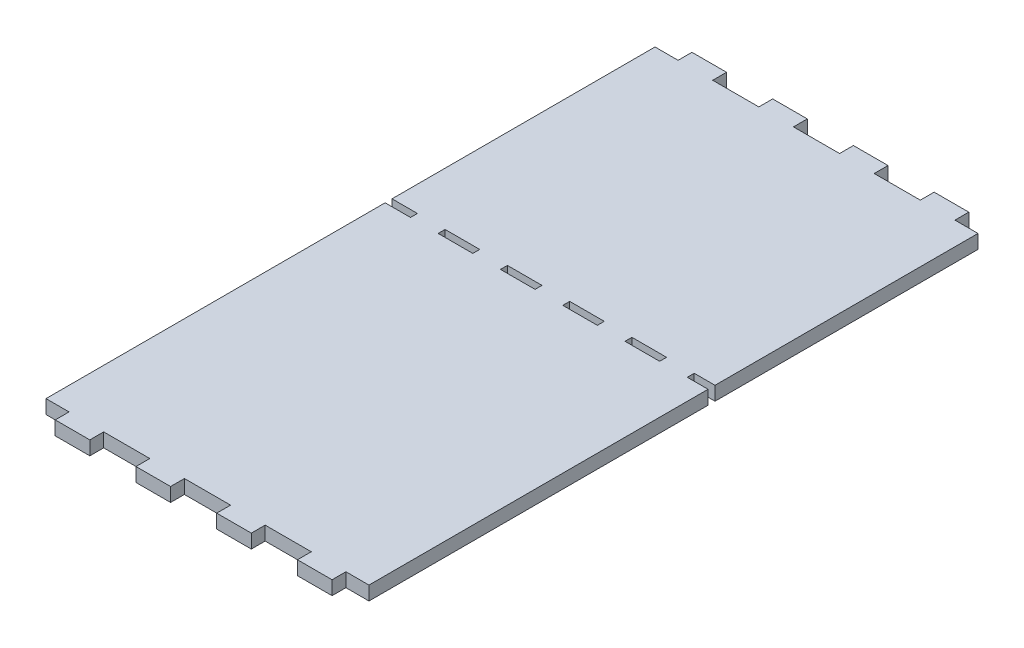
SolidWorks part; units mm, degrees
ref_plane "Plan de face" through (0, 0, 0) normal (0, 0, 1) x (1, 0, 0)
ref_plane "Plan de dessus" through (0, 0, 0) normal (0, 1, 0) x (1, 0, 0)
ref_plane "Plan de droite" through (0, 0, 0) normal (1, 0, 0) x (0, 0, -1)
sketch "Esquisse1" plane through (0, 0, 0) normal (0, 1, 0) x (1, 0, 0)
  line L0 (-140, 138) -> (0, 138) construction
  line L1 (0, 0) -> (-140, 0)
  line L2 (0, 0) -> (0, 276)
  line L3 (0, 276) -> (-140, 276)
  line L4 (-140, 0) -> (-140, 276)
  line L5 (-140, 0) -> (-115, 0)
  line L6 (-140, 0) -> (-140, 6)
  line L7 (-140, 0) -> (-130, 0)
  line L8 (-115, 0) -> (-115, 6)
  line L9 (-115, 6) -> (-95, 6)
  line L10 (-115, 6) -> (-115, 0)
  line L11 (-115, 0) -> (-95, 0)
  line L12 (-95, 6) -> (-95, 0)
  line L13 (-95, 6) -> (-80, 6)
  line L14 (-95, 6) -> (-95, 0)
  line L15 (-95, 0) -> (-80, 0)
  line L16 (-80, 6) -> (-80, 0)
  line L17 (-80, 6) -> (-60, 6)
  line L18 (-80, 6) -> (-80, 0)
  line L19 (-80, 0) -> (-60, 0)
  line L20 (-60, 6) -> (-60, 0)
  line L21 (-60, 6) -> (-45, 6)
  line L22 (-60, 6) -> (-60, 0)
  line L23 (-60, 0) -> (-45, 0)
  line L24 (-45, 6) -> (-45, 0)
  line L25 (-45, 6) -> (-25, 6)
  line L26 (-45, 6) -> (-45, 0)
  line L27 (-45, 0) -> (-25, 0)
  line L28 (-25, 6) -> (-25, 0)
  line L29 (-25, 6) -> (-10, 6)
  line L30 (-25, 6) -> (-25, 0)
  line L31 (-25, 0) -> (-10, 0)
  line L32 (-10, 6) -> (-10, 0)
  line L33 (-10, 6) -> (0, 6)
  line L34 (-10, 6) -> (-10, 0)
  line L35 (-140, 6) -> (-130, 6)
  line L36 (-10, 6) -> (-10, 0)
  line L37 (-140, 6) -> (-140, 0)
  line L38 (-140, 0) -> (-130, 0)
  line L39 (-130, 6) -> (-130, 0)
  line L40 (-10, 270) -> (0, 270)
  line L41 (-140, 0) -> (-140, 6)
  line L43 (-130, 0) -> (-130, 6)
  line L44 (-130, 6) -> (-115, 6)
  line L45 (-130, 6) -> (-130, 0)
  line L46 (-130, 0) -> (-115, 0)
  line L47 (-115, 6) -> (-115, 0)
  line L48 (0, 0) -> (0, 6)
  line L51 (0, 0) -> (0, 6)
  line L52 (0, 276) -> (0, 270)
  line L56 (-115, 270) -> (-115, 276)
  line L57 (-130, 276) -> (-115, 276)
  line L58 (-130, 270) -> (-130, 276)
  line L59 (-130, 270) -> (-115, 270)
  line L60 (-130, 276) -> (-130, 270)
  line L61 (-140, 270) -> (-130, 270)
  line L62 (-140, 276) -> (-140, 270)
  line L69 (-10, 270) -> (-10, 276)
  line L71 (-10, 270) -> (-10, 276)
  line L72 (-25, 276) -> (-10, 276)
  line L73 (-25, 270) -> (-25, 276)
  line L74 (-25, 270) -> (-10, 270)
  line L75 (-25, 270) -> (-25, 276)
  line L76 (-45, 276) -> (-25, 276)
  line L77 (-45, 270) -> (-45, 276)
  line L78 (-45, 270) -> (-25, 270)
  line L79 (-45, 270) -> (-45, 276)
  line L80 (-60, 276) -> (-45, 276)
  line L81 (-60, 270) -> (-60, 276)
  line L82 (-60, 270) -> (-45, 270)
  line L83 (-60, 270) -> (-60, 276)
  line L84 (-80, 276) -> (-60, 276)
  line L85 (-80, 270) -> (-80, 276)
  line L86 (-80, 270) -> (-60, 270)
  line L87 (-80, 270) -> (-80, 276)
  line L88 (-95, 276) -> (-80, 276)
  line L89 (-95, 270) -> (-95, 276)
  line L90 (-95, 270) -> (-80, 270)
  line L91 (-95, 270) -> (-95, 276)
  line L92 (-115, 276) -> (-95, 276)
  line L93 (-115, 270) -> (-115, 276)
  line L94 (-115, 270) -> (-95, 270)
  line L95 (-115, 276) -> (-115, 270)
  line L96 (-140, 276) -> (-130, 276)
  line L97 (-140, 276) -> (-140, 270)
  line L98 (-140, 276) -> (-115, 276)
  line L99 (0, 276) -> (-140, 276)
  dimension "D1" = 140
  dimension "D2" = 276
  dimension "D3" = 15
  dimension "D4" = 20
  dimension "D5" = 10
  dimension "D6" = 6
extrude "Boss.-Extru.1" add sketch "Esquisse1" along normal blind 6
sketch "Esquisse2" plane through (0, 0, 0) normal (0, -1, 0) x (1, 0, 0)
  line L1 (-9, -156) -> (6, -156)
  line L2 (-9, -156) -> (-9, -153)
  line L3 (-9, -153) -> (6, -153)
  line L4 (6, -156) -> (6, -153)
  line L5 (-21, -153) -> (-36, -153)
  line L6 (-21, -153) -> (-21, -156)
  line L7 (-21, -156) -> (-36, -156)
  line L8 (-36, -153) -> (-36, -156)
  line L9 (-48, -153) -> (-63, -153)
  line L10 (-48, -153) -> (-48, -156)
  line L11 (-48, -156) -> (-63, -156)
  line L12 (-63, -153) -> (-63, -156)
  line L13 (-75, -153) -> (-90, -153)
  line L14 (-75, -153) -> (-75, -156)
  line L15 (-75, -156) -> (-90, -156)
  line L16 (-90, -153) -> (-90, -156)
  line L17 (-102, -153) -> (-117, -153)
  line L18 (-102, -153) -> (-102, -156)
  line L19 (-102, -156) -> (-117, -156)
  line L20 (-117, -153) -> (-117, -156)
  line L21 (-129, -153) -> (-144, -153)
  line L22 (-129, -153) -> (-129, -156)
  line L23 (-129, -156) -> (-144, -156)
  line L24 (-144, -153) -> (-144, -156)
extrude "Enlèv. mat.-Extru.1" cut sketch "Esquisse2" against normal blind 6
